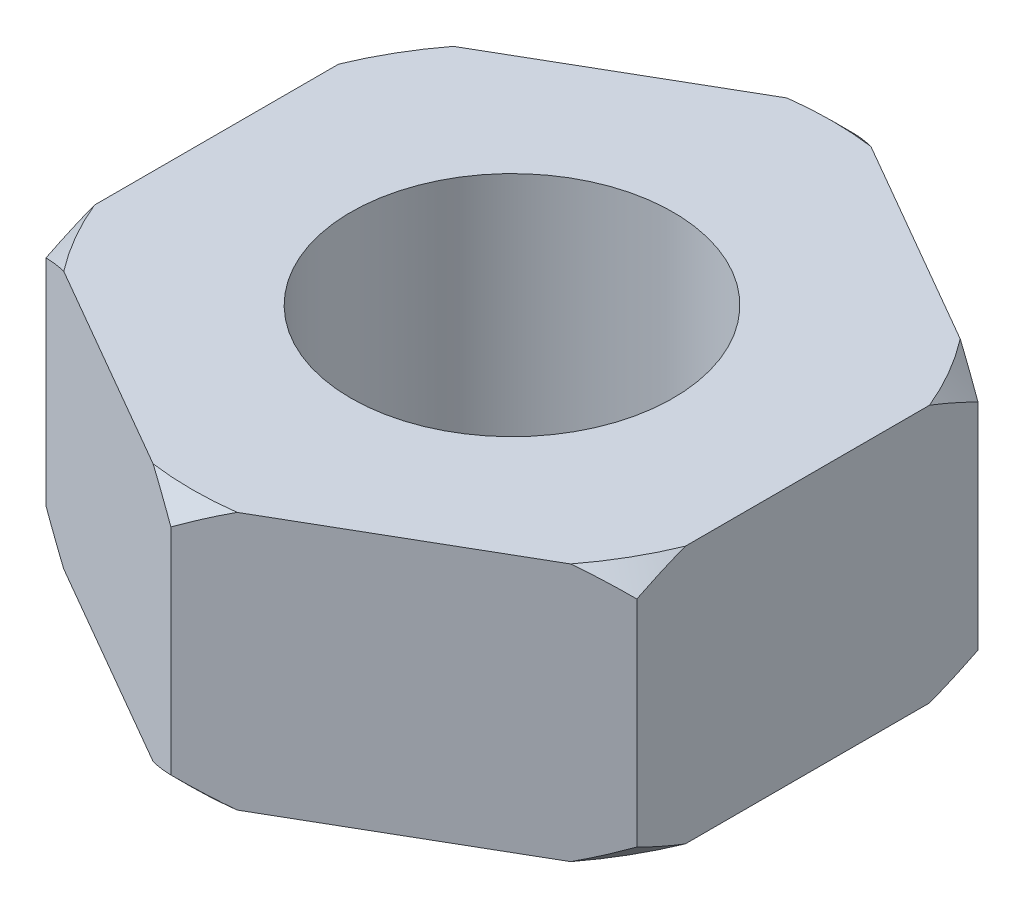
SolidWorks part; units mm, degrees
ref_plane "Front Plane" through (0, 0, 0) normal (0, 0, 1) x (1, 0, 0)
ref_plane "Top Plane" through (0, 0, 0) normal (0, 1, 0) x (1, 0, 0)
ref_plane "Right Plane" through (0, 0, 0) normal (1, 0, 0) x (0, 0, -1)
sketch "Sketch1" plane through (0, 0, 0) normal (0, 1, 0) x (1, 0, 0)
  line L1 (0, 3.1754) -> (-2.75, 1.5877)
  line L2 (-2.75, 1.5877) -> (-2.75, -1.5877)
  line L3 (-2.75, -1.5877) -> (0, -3.1754)
  line L4 (0, -3.1754) -> (2.75, -1.5877)
  line L5 (2.75, -1.5877) -> (2.75, 1.5877)
  line L6 (2.75, 1.5877) -> (0, 3.1754)
  circle A0 centre (0, 0) radius 2.75 construction
  circle A1 centre (0, 0) radius 1.5
  dimension "D1" = 5.5
  dimension "D2" = 3
extrude "Boss-Extrude1" add sketch "Sketch1" along normal blind 2.4
cosmetic thread "Cosmetic Thread1" parameters "D2"=4
sketch "Sketch3" plane through (0, 0, 0) normal (1, 0, 0) x (0, 0, -1)
  line L0 (3.1754, 2.4) -> (3.1754, 2.2)
  line L1 (3.1754, 2.4) -> (3.1754, 0) construction
  line L2 (3.1754, 2.2) -> (2.9754, 2.4)
  line L3 (3.1754, 2.4) -> (1.5877, 2.4) construction
  line L4 (2.9754, 2.4) -> (3.1754, 2.4)
  line L5 (3.1754, 0.2) -> (3.1754, 0)
  line L6 (3.1754, 0) -> (2.9754, 0)
  line L7 (3.1754, 0) -> (1.5877, 0) construction
  line L8 (2.9754, 0) -> (3.1754, 0.2)
  line L9 (0, 0) -> (0, 1.1169)
  dimension "D1" = 45
  dimension "D2" = 0.2
  dimension "D3" = 45
  dimension "D4" = 0.2
revolve "Cut-Revolve3" cut sketch "Sketch3" angle 360 about L9
